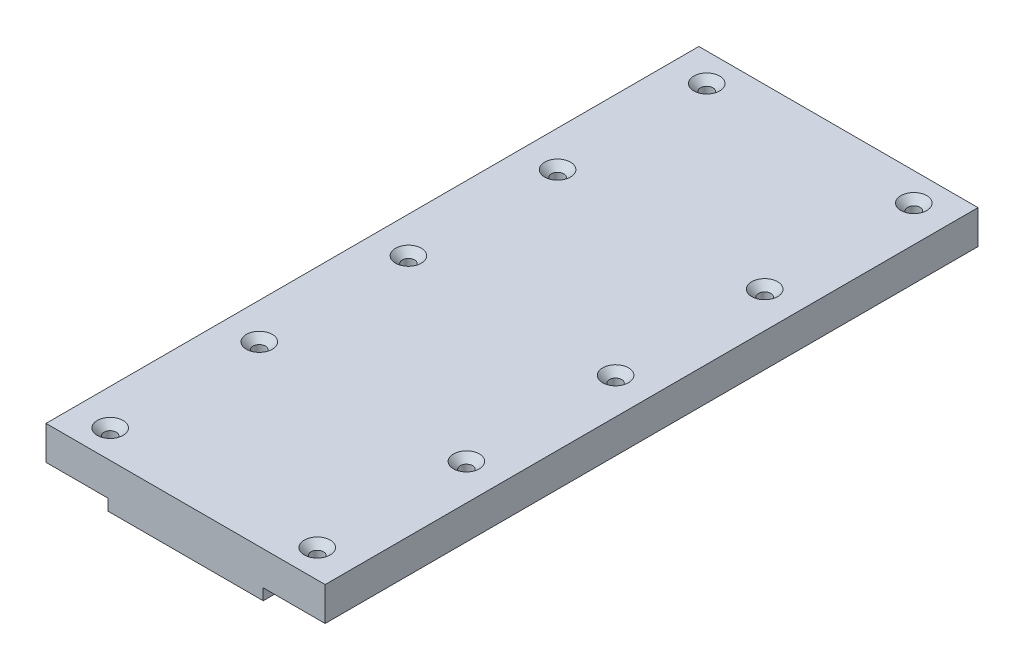
SolidWorks part; units mm, degrees
ref_plane "Alzado" through (0, 0, 0) normal (0, 0, 1) x (1, 0, 0)
ref_plane "Planta" through (0, 0, 0) normal (0, 1, 0) x (1, 0, 0)
ref_plane "Vista lateral" through (0, 0, 0) normal (1, 0, 0) x (0, 0, -1)
sketch "Croquis1" plane through (0, 0, 0) normal (0, 0, 1) x (1, 0, 0)
  line L6 (0, 0) -> (-55, 0)
  line L7 (-55, 0) -> (-55, -10)
  line L8 (-55, -10) -> (-193, -10)
  line L9 (-193, -10) -> (-193, 0)
  line L10 (-193, 0) -> (-248, 0)
  line L11 (-248, 0) -> (-248, 30)
  line L12 (-248, 30) -> (0, 30)
  line L13 (0, 30) -> (0, 0)
  dimension "D1" = 138
  dimension "D2" = 248
  dimension "D3" = 40
  dimension "D4" = 10
extrude "Saliente-Extruir1" add sketch "Croquis1" against normal blind 580
sketch "Croquis2" plane through (0, 30, 0) normal (0, 1, 0) x (1, 0, 0)
  line L0 (-216, 580) -> (-216, 0) construction
  line L1 (0, 580) -> (-248, 580) construction
  line L2 (0, 0) -> (-248, 0) construction
  line L3 (-32, 580) -> (-32, 0) construction
  line L4 (-248, 580) -> (-248, 0) construction
  line L5 (-216, 555) -> (-32, 555) construction
  line L6 (-216, 555) -> (-216, 422.5) construction
  circle A0 centre (-216, 555) radius 5.5
  circle A1 centre (-32, 555) radius 5.5
  circle A2 centre (-32, 422.5) radius 5.5
  circle A3 centre (-32, 290) radius 5.5
  circle A4 centre (-32, 157.5) radius 5.5
  circle A5 centre (-32, 25) radius 5.5
  circle A6 centre (-216, 422.5) radius 5.5
  circle A7 centre (-216, 290) radius 5.5
  circle A8 centre (-216, 157.5) radius 5.5
  circle A9 centre (-216, 25) radius 5.5
  dimension "D3" = 11
  dimension "D1" = 184
  dimension "D2" = 32
  dimension "D4" = 25
  dimension "D7" = 184
  dimension "D8" = 132.5
  dimension "D5" = 2
  dimension "D6" = 5
extrude "Cortar-Extruir1" cut sketch "Croquis2" against normal up to next
chamfer "Chaflán1" distance 6 angle 45 10 edges at (-32, 30, -19.5) (-32, 30, -152) (-32, 30, -284.5) (-32, 30, -417) (-32, 30, -549.5) (-216, 30, -549.5) (-216, 30, -417) (-216, 30, -284.5) (-216, 30, -152) (-216, 30, -19.5)
